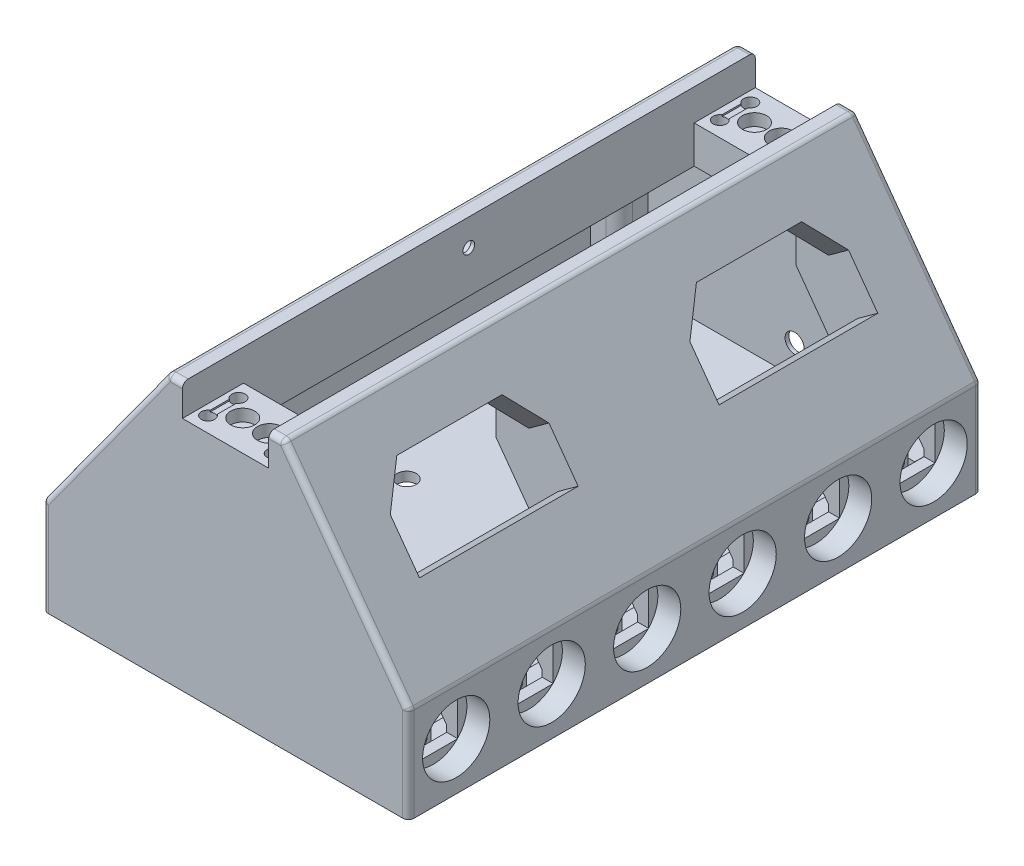
SolidWorks part; units mm, degrees
ref_plane "Front Plane" through (0, 0, 0) normal (0, 0, 1) x (1, 0, 0)
ref_plane "Top Plane" through (0, 0, 0) normal (0, 1, 0) x (1, 0, 0)
ref_plane "Right Plane" through (0, 0, 0) normal (1, 0, 0) x (0, 0, -1)
sketch "Sketch1" plane through (0, 0, 0) normal (0, 0, 1) x (1, 0, 0)
  line L0 (0, 0) -> (0, 70) construction
  line L1 (47.8944, 0) -> (-47.8944, 0)
  line L2 (-47.8944, 0) -> (-47.8944, 25)
  line L3 (-47.8944, 25) -> (-15.2, 70)
  line L4 (15.2, 70) -> (-15.2, 70) construction
  line L5 (45.8944, 2) -> (-45.8944, 2)
  line L6 (-45.8944, 2) -> (-45.8944, 23.4995)
  line L7 (-45.8944, 23.4995) -> (-25.1833, 52.0059)
  line L8 (11.3, 70) -> (11.3, 61.8)
  line L11 (-15.2, 70) -> (-11.3, 70)
  line L12 (-11.3, 70) -> (-11.3, 61.8)
  line L13 (-11.3, 61.8) -> (11.3, 61.8)
  line L14 (15.2, 70) -> (11.3, 70)
  line L16 (45.8944, 23.4995) -> (25.1833, 52.0059)
  line L17 (45.8944, 2) -> (45.8944, 23.4995)
  line L18 (47.8944, 25) -> (15.2, 70)
  line L19 (47.8944, 0) -> (47.8944, 25)
  line L20 (-25.1833, 52.0059) -> (25.1833, 52.0059)
  point P19 (0, 61.8)
  point P21 (0, 50.577)
  point P24 (0, 2)
  dimension "D1" = 15.2
  dimension "D2" = 54
  dimension "D3" = 8.2
  dimension "D4" = 2.5
  dimension "D5" = 2
  dimension "D6" = 25
  dimension "D7" = 70
  dimension "D8" = 47.8944
  dimension "D9" = 2
  dimension "D12" = 11.3
extrude "Boss-Extrude2" add sketch "Sketch1" along normal blind 150
sketch "Sketch3" plane through (0, 61.8, 0) normal (0, 1, 0) x (1, 0, 0)
  line L0 (11.3, -150) -> (11.3, 0) construction
  line L1 (11.3, -16) -> (-11.3, -16)
  line L2 (11.3, -16) -> (11.3, -134)
  line L3 (11.3, -134) -> (-11.3, -134)
  line L4 (-11.3, -16) -> (-11.3, -134)
  line L5 (-11.3, -150) -> (-11.3, 0) construction
  line L7 (-11.3, 0) -> (11.3, 0) construction
  line L8 (-8.6, -4) -> (-8.6, -12) construction
  line L9 (-11.3, -8) -> (0, -8) construction
  line L10 (0, -8) -> (0, 0) construction
  line L11 (-11.3, -75) -> (11.3, -75) construction
  circle A0 centre (-8.6, -12) radius 1.75
  circle A2 centre (-8.6, -4) radius 1.75
  circle A3 centre (8.6, -12) radius 1.75
  circle A4 centre (8.6, -4) radius 1.75
  circle A5 centre (8.6, -138) radius 1.75
  circle A6 centre (8.6, -146) radius 1.75
  circle A7 centre (-8.6, -146) radius 1.75
  circle A8 centre (-8.6, -138) radius 1.75
  circle A9 centre (-3.5, -8) radius 3 construction
  point P9 (11.3, -75)
  point P17 (-8.6, -8)
  dimension "D2" = 3.5
  dimension "D6" = 6
  dimension "D1" = 16
  dimension "D3" = 8
  dimension "D4" = 8
  dimension "D5" = 8.6
  dimension "D7" = 3.5
extrude "Cut-Extrude1" cut sketch "Sketch3" against normal up to next
ref_plane "Plane1" through (-12.3, 0, 0) normal (1, 0, 0) x (0, 0, -1)
ref_plane "Plane2" through (0, 0, 75) normal (0, 0, 1) x (1, 0, 0)
sketch "Sketch12" plane through (0, 0, 0) normal (0, 0, -1) x (-1, 0, 0)
  line L0 (-38.9919, 8) -> (-14.3, 41.9855)
  line L1 (-38.9919, 8) -> (-38.9919, 2)
  line L3 (-45.8944, 2) -> (45.8944, 2) construction
  line L4 (-47.8944, 25) -> (-15.2, 70) construction
  line L6 (-45.8944, 23.4995) -> (-25.1833, 52.0059) construction
  line L7 (-45.8944, 23.4995) -> (-25.1833, 52.0059)
  line L8 (-45.8944, 2) -> (-45.8944, 23.4995) construction
  line L9 (-45.8944, 2) -> (-45.8944, 23.4995)
  line L10 (-38.9919, 2) -> (-45.8944, 2)
  line L11 (-14.3, 41.9855) -> (-14.3, 52.0059)
  line L12 (25.1833, 52.0059) -> (-25.1833, 52.0059) construction
  line L13 (-11.3, 70) -> (-11.3, 61.8) construction
  line L14 (-25.1833, 52.0059) -> (-14.3, 52.0059)
  dimension "D1" = 17.1946
  dimension "D2" = 6
  dimension "D3" = 3
extrude "Boss-Extrude4" add sketch "Sketch12" against normal up to surface (150 mm away) up to face at (0, 25.8351, 150)
sketch "Sketch5" plane through (-11.3, 0, 0) normal (1, 0, 0) x (0, 0, -1)
  line L0 (-150, 70) -> (0, 70) construction
  line L1 (-75, 63) -> (-75, 70) construction
  circle A0 centre (-75, 63) radius 1.52
  dimension "D2" = 3.04
  dimension "D1" = 7
extrude "Cut-Extrude2" cut sketch "Sketch5" against normal through all
sketch "Sketch6" plane through (-11.3, 0, 0) normal (1, 0, 0) x (0, 0, -1)
  circle A0 centre (-75, 63) radius 1.52 construction
  circle A1 centre (-75, 63) radius 1.52
extrude "Cut-Extrude3" cut sketch "Sketch6" along normal offset from surface (26.6 mm away) 4 up to face at (11.3, 61.4015, 75) offset beyond the face yes
sketch "Sketch7" plane through (-12.3, 0, 0) normal (1, 0, 0) x (0, 0, -1)
  circle A0 centre (-75, 63) radius 1.52 construction
  circle A1 centre (-75, 63) radius 1.52 construction
  circle A2 centre (-75, 63) radius 2.8
  dimension "D1" = 5.6
extrude "Cut-Extrude4" cut sketch "Sketch7" against normal through all
sketch "Sketch10" plane through (-43.2355, 31.4124, 0) normal (-0.809, 0.5878, 0) x (0, 0, 1)
  line L0 (75, -7.9262) -> (75, 47.6969) construction
  line L1 (67.15, 32.6969) -> (82.85, 32.6969)
  line L2 (67.15, 32.6969) -> (67.15, 3.1969)
  line L3 (67.15, 3.1969) -> (82.85, 3.1969)
  line L4 (82.85, 32.6969) -> (82.85, 3.1969)
  line L5 (150, -7.9262) -> (0, -7.9262) construction
  line L6 (150, 47.6969) -> (0, 47.6969) construction
  point P10 (75, 32.6969)
  dimension "D1" = 29.5
  dimension "D2" = 15.7
  dimension "D3" = 15
extrude "Cut-Extrude5" cut sketch "Sketch10" against normal up to next
sketch "Sketch11" plane through (43.2355, 31.4124, 0) normal (0.809, 0.5878, 0) x (0, 0, -1)
  line L0 (-150, -7.9262) -> (-150, 47.6969) construction
  line L1 (-135, 34.6969) -> (-93.45, 34.6969)
  line L2 (-135, 34.6969) -> (-135, 12.6969)
  line L3 (-135, 12.6969) -> (-93.45, 12.6969)
  line L4 (-93.45, 34.6969) -> (-93.45, 12.6969)
  line L5 (-150, 47.6969) -> (0, 47.6969) construction
  dimension "D1" = 41.55
  dimension "D2" = 22
  dimension "D3" = 15
  dimension "D4" = 13
extrude "Cut-Extrude6" cut sketch "Sketch11" against normal up to next
sketch "Sketch13" plane through (-7.463, 10.272, 0) normal (-0.5878, 0.809, 0) x (0.809, 0.5878, 0)
  line L0 (36.2474, -135) -> (53.442, -135) construction
  line L1 (36.2474, -93.45) -> (46.942, -93.45)
  line L2 (36.2474, -93.45) -> (36.2474, -135)
  line L3 (36.2474, -135) -> (46.942, -135)
  line L4 (46.942, -93.45) -> (46.942, -135)
  line L5 (53.442, -135) -> (53.442, -93.45) construction
  dimension "D1" = 6.5
extrude "Cut-Extrude7" cut sketch "Sketch13" against normal blind 12
sketch "Sketch14" plane through (-20.3943, 28.0703, 0) normal (0.5878, -0.809, 0) x (0.809, 0.5878, 0)
  line L0 (46.942, 93.45) -> (53.442, 93.45) construction
  line L1 (53.442, 93.45) -> (46.942, 93.45)
  line L2 (53.442, 93.45) -> (53.442, 100.45)
  line L3 (53.442, 100.45) -> (46.942, 100.45)
  line L4 (46.942, 93.45) -> (46.942, 100.45)
  line L5 (53.442, 114.225) -> (36.2474, 114.225) construction
  line L6 (53.442, 93.45) -> (53.442, 135) construction
  line L7 (36.2474, 93.45) -> (36.2474, 135) construction
  line L8 (46.942, 135) -> (46.942, 128)
  line L9 (53.442, 128) -> (46.942, 128)
  line L10 (53.442, 135) -> (53.442, 128)
  line L11 (53.442, 135) -> (46.942, 135)
  dimension "D1" = 7
extrude "Boss-Extrude5" add sketch "Sketch14" along normal blind 9
sketch "Sketch18" plane through (47.8944, 0, 0) normal (1, 0, 0) x (0, 0, -1)
  line L0 (-150, 0) -> (-150, 25) construction
  line L1 (-137.5, 12.5) -> (-150, 12.5) construction
  line L2 (-150, 25) -> (0, 25) construction
  line L3 (-150, 25) -> (0, 25) construction
  circle A0 centre (-137.5, 12.5) radius 8.8
  dimension "D1" = 17.6
  dimension "D2" = 150
  dimension "D3" = 12.5
extrude "Cut-Extrude8" cut sketch "Sketch18" against normal blind 6
sketch "Sketch19" plane through (43.2355, 31.4124, 0) normal (0.809, 0.5878, 0) x (0, 0, -1)
  line L0 (-135, 25.6969) -> (-128, 34.6969)
  line L1 (-128, 34.6969) -> (-128, 25.6969)
  line L2 (-128, 25.6969) -> (-135, 25.6969)
  line L3 (-114.225, 34.6969) -> (-114.225, 12.6969) construction
  line L4 (-100.45, 34.6969) -> (-128, 34.6969) construction
  line L5 (-135, 12.6969) -> (-93.45, 12.6969) construction
  line L6 (-100.45, 34.6969) -> (-100.45, 25.6969)
  line L7 (-93.45, 25.6969) -> (-100.45, 34.6969)
  line L8 (-100.45, 25.6969) -> (-93.45, 25.6969)
extrude "Cut-Extrude9" cut sketch "Sketch19" against normal up to next
mirror "Mirror1" about plane through (0, 0, 75) normal (0, 0, 1) of "Boss-Extrude5", "Cut-Extrude9", "Cut-Extrude7", "Cut-Extrude6"
sketch "Sketch21" plane through (0, 61.8, 0) normal (0, 1, 0) x (1, 0, 0)
  line L0 (-6.85, -12) -> (-6.85, -4)
  line L1 (-10.35, -4) -> (-10.35, -12)
  line L2 (0, 0) -> (0, -16) construction
  line L3 (-11.3, 0) -> (11.3, 0) construction
  line L4 (11.3, -16) -> (-11.3, -16) construction
  line L5 (10.35, -4) -> (10.35, -12)
  line L6 (6.85, -12) -> (6.85, -4)
  circle A0 centre (-8.6, -4) radius 1.75 construction
  arc A1 (-10.35, -4) -> (-6.85, -4) centre (-8.6, -4) ccw
  circle A2 centre (-8.6, -12) radius 1.75 construction
  arc A3 (-6.85, -12) -> (-10.35, -12) centre (-8.6, -12) ccw
  arc A4 (6.85, -12) -> (10.35, -12) centre (8.6, -12) cw
  arc A5 (10.35, -4) -> (6.85, -4) centre (8.6, -4) cw
extrude "Cut-Extrude10" [suppressed] cut sketch "Sketch21" against normal blind 0.4
sketch "Sketch25" plane through (0, 0, 150) normal (0, 0, 1) x (1, 0, 0)
  line L10 (-11.3, 61.8) -> (-11.3, 70)
  line L11 (-11.3, 70) -> (-15.2, 70)
  line L12 (-15.2, 70) -> (-47.8944, 25)
  line L13 (-47.8944, 25) -> (-47.8944, 0)
  line L14 (-47.8944, 0) -> (47.8944, 0)
  line L15 (47.8944, 0) -> (47.8944, 25)
  line L16 (47.8944, 25) -> (15.2, 70)
  line L17 (15.2, 70) -> (11.3, 70)
  line L18 (11.3, 70) -> (11.3, 61.8)
  line L19 (11.3, 61.8) -> (-11.3, 61.8)
  line L20 (-11.3, 61.8) -> (-11.3, 70)
  line L21 (-11.3, 70) -> (-15.2, 70)
  line L22 (-15.2, 70) -> (-47.8944, 25)
  line L23 (-47.8944, 25) -> (-47.8944, 0)
  line L24 (-47.8944, 0) -> (47.8944, 0)
  line L25 (47.8944, 0) -> (47.8944, 25)
  line L26 (47.8944, 25) -> (15.2, 70)
  line L27 (15.2, 70) -> (11.3, 70)
  line L28 (11.3, 70) -> (11.3, 61.8)
  line L29 (11.3, 61.8) -> (-11.3, 61.8)
  dimension "D1" = 0
extrude "Boss-Extrude6" add sketch "Sketch25" against normal blind 1
mirror "Mirror3" about plane through (0, 0, 75) normal (0, 0, 1) of "Boss-Extrude6"
sketch "Sketch27" plane through (0, 2, 0) normal (0, 1, 0) x (1, 0, 0)
  line L0 (-41.8944, -145) -> (-41.8944, -149) construction
  line L1 (-45.8944, -149) -> (38.9919, -149) construction
  line L2 (-41.8944, -145) -> (-45.8944, -145) construction
  line L3 (-45.8944, -149) -> (-45.8944, -1) construction
  line L4 (-45.8944, -75) -> (34.8364, -75) construction
  line L5 (-15.8944, -1) -> (-15.8944, -149) construction
  line L8 (-41.8944, -5) -> (-45.8944, -5) construction
  line L9 (-41.8944, -141.5) -> (-45.8944, -141.5)
  line L10 (-38.3944, -145) -> (-38.3944, -149)
  line L11 (-45.8944, -141.5) -> (-45.8944, -149)
  line L12 (-45.8944, -149) -> (-38.3944, -149)
  line L13 (-41.8944, -5) -> (-41.8944, -1) construction
  line L14 (-45.8944, -1) -> (-38.3944, -1)
  line L15 (-45.8944, -8.5) -> (-45.8944, -1)
  line L16 (-38.3944, -5) -> (-38.3944, -1)
  line L17 (-41.8944, -8.5) -> (-45.8944, -8.5)
  line L18 (38.9919, -1) -> (-45.8944, -1) construction
  circle A0 centre (-41.8944, -145) radius 2
  arc A1 (-38.3944, -145) -> (-41.8944, -141.5) centre (-41.8944, -145) ccw
  arc A2 (-38.3944, -5) -> (-41.8944, -8.5) centre (-41.8944, -5) cw
  circle A3 centre (-41.8944, -5) radius 2
  dimension "D1" = 4
  dimension "D2" = 7
  dimension "D3" = 4
  dimension "D4" = 4
  dimension "D5" = 30
extrude "Boss-Extrude7" add sketch "Sketch27" along normal up to surface (27.005 mm away)
sketch "Sketch28" plane through (0, 2, 0) normal (0, 1, 0) x (1, 0, 0)
  line L4 (38.9919, -149) -> (38.9919, -1)
  line L5 (38.9919, -1) -> (-38.3944, -1)
  line L6 (-45.8944, -8.5) -> (-45.8944, -141.5)
  line L7 (-38.3944, -149) -> (38.9919, -149)
  line L8 (38.9919, -149) -> (38.9919, -1)
  line L9 (38.9919, -1) -> (-38.3944, -1)
  line L10 (-45.8944, -8.5) -> (-45.8944, -141.5)
  line L11 (-38.3944, -149) -> (38.9919, -149)
  line L16 (-45.8944, -141.5) -> (-41.8944, -141.5)
  line L18 (-45.8944, -141.5) -> (-41.8944, -141.5)
  line L20 (-38.3944, -145) -> (-38.3944, -149)
  line L22 (-38.3944, -145) -> (-38.3944, -149)
  line L24 (-38.3944, -1) -> (-38.3944, -5)
  line L25 (-38.3944, -1) -> (-38.3944, -5)
  line L26 (-41.8944, -8.5) -> (-45.8944, -8.5)
  line L27 (-41.8944, -8.5) -> (-45.8944, -8.5)
  arc A2 (-38.3944, -145) -> (-41.8944, -141.5) centre (-41.8944, -145) ccw
  arc A4 (-38.3944, -145) -> (-41.8944, -141.5) centre (-41.8944, -145) ccw
  arc A6 (-41.8944, -8.5) -> (-38.3944, -5) centre (-41.8944, -5) ccw
  arc A7 (-41.8944, -8.5) -> (-38.3944, -5) centre (-41.8944, -5) ccw
  dimension "D1" = 0
extrude "Cut-Extrude13" cut sketch "Sketch28" against normal through all
sketch "Sketch29" plane through (0, 2, 0) normal (0, 1, 0) x (1, 0, 0)
  circle A1 centre (-41.8944, -5) radius 2
  circle A2 centre (-41.8944, -5) radius 2
  circle A3 centre (-41.8944, -145) radius 2
  circle A4 centre (-41.8944, -145) radius 2
  dimension "D1" = 0
  dimension "D2" = 0
extrude "Cut-Extrude14" cut sketch "Sketch29" against normal through all
sketch "Sketch30" plane through (0, 0, 0) normal (0, -1, 0) x (1, 0, 0)
  line L0 (-38.3944, 149) -> (-45.8944, 149)
  line L1 (-45.8944, 149) -> (-45.8944, 141.5)
  line L3 (-45.8944, 8.5) -> (-45.8944, 141.5) construction
  line L4 (-38.3944, 145) -> (-38.3944, 149) construction
  line L5 (-38.3944, 145) -> (-38.3944, 149)
  line L6 (-45.8944, 141.5) -> (-41.8944, 141.5) construction
  line L7 (-45.8944, 141.5) -> (-41.8944, 141.5)
  line L8 (38.5, 75) -> (-38.5, 75) construction
  line L9 (-45.8944, 8.5) -> (-41.8944, 8.5)
  line L10 (-38.3944, 5) -> (-38.3944, 1)
  line L11 (-45.8944, 1) -> (-45.8944, 8.5)
  line L12 (-38.3944, 1) -> (-45.8944, 1)
  arc A0 (-41.8944, 141.5) -> (-38.3944, 145) centre (-41.8944, 145) ccw construction
  arc A1 (-41.8944, 141.5) -> (-38.3944, 145) centre (-41.8944, 145) ccw
  arc A2 (-41.8944, 8.5) -> (-38.3944, 5) centre (-41.8944, 5) cw
extrude "D" cut sketch "Sketch30" against normal blind 2.5
sketch "Sketch31" plane through (0, 0, 149) normal (0, 0, -1) x (-1, 0, 0)
  line L6 (45.8944, 0) -> (-38.9919, 0) construction
  line L7 (-38.9919, 0) -> (-37.1919, 0)
  line L8 (-38.9919, 0) -> (-38.9919, 3)
  line L9 (-38.9919, 3) -> (-37.5919, 3)
  line L10 (-37.1919, 0) -> (-37.1919, 2.6)
  arc A1 (-37.5919, 3) -> (-37.1919, 2.6) centre (-37.5919, 2.6) cw
  point P13 (-37.1919, 4.5)
  point P16 (-37.1919, 3)
  dimension "D1" = 3
  dimension "D3" = 1.8
extrude "Boss-Extrude8" add sketch "Sketch31" along normal blind 1.4
mirror "Mirror4" about plane through (0, 0, 75) normal (0, 0, 1) of "Boss-Extrude8"
sketch "Sketch33" plane through (0, 0, 1) normal (0, 0, 1) x (1, 0, 0)
  line L0 (0, 0) -> (0, 10) construction
  circle A0 centre (0, 10) radius 2.5
  dimension "D1" = 5
  dimension "D2" = 10
extrude "Cut-Extrude16" cut sketch "Sketch33" against normal through all
fillet "Fillet1" radius 1.5 16 edges at (-13.25, 70, 0) (-13.25, 70, 150) (13.25, 70, 0) (13.25, 70, 150) (47.8944, 12.5, 0) (47.8944, 12.5, 150) (-47.8944, 12.5, 0) (-47.8944, 12.5, 150) (-31.5472, 47.5, 0) (-31.5472, 47.5, 150) (31.5472, 47.5, 0) (31.5472, 47.5, 150) (47.8944, 25, 75) (-47.8944, 25, 75) (-15.2, 70, 75) (15.2, 70, 75)
sketch "Sketch34" plane through (0, 61.8, 0) normal (0, 1, 0) x (1, 0, 0)
  line L0 (-3.5, 0) -> (-3.5, -16) construction
  line L1 (-11.3, 0) -> (11.3, 0) construction
  line L2 (11.3, -16) -> (-11.3, -16) construction
  line L3 (3.5, -8) -> (-3.5, -8) construction
  line L4 (0, 0) -> (0, -8) construction
  circle A0 centre (-3.5, -8) radius 3.15
  circle A1 centre (3.5, -8) radius 3.15
  point P11 (0, -8)
  dimension "D1" = 6.3
  dimension "D2" = 7
  dimension "D3" = 8
extrude "Cut-Extrude17" cut sketch "Sketch34" against normal blind 3.15
mirror "Mirror6" about plane through (0, 0, 75) normal (0, 0, 1) of "Cut-Extrude17"
sketch "Sketch35" plane through (41.8944, 0, 0) normal (1, 0, 0) x (0, 0, -1)
  line L1 (-143.9, 18.675) -> (-131.1, 18.675)
  line L2 (-143.9, 18.675) -> (-143.9, 6.325)
  line L3 (-143.9, 6.325) -> (-131.1, 6.325)
  line L4 (-131.1, 18.675) -> (-131.1, 6.325)
  line L5 (-143.9, 18.675) -> (-131.1, 6.325) construction
  line L6 (-143.9, 6.325) -> (-131.1, 18.675) construction
  circle A0 centre (-137.5, 12.5) radius 8.8 construction
  point P0 (-137.5, 12.5)
  dimension "D1" = 12.35
  dimension "D2" = 12.8
extrude "Cut-Extrude18" cut sketch "Sketch35" against normal up to next
sketch "Sketch38" plane through (38.9919, 0, 0) normal (-1, 0, 0) x (0, 0, 1)
  line L1 (139.75, 4.63) -> (135.25, 4.63)
  line L2 (139.75, 4.63) -> (139.75, 18.675)
  line L3 (139.75, 18.675) -> (135.25, 18.675)
  line L4 (135.25, 4.63) -> (135.25, 18.675)
  line L5 (143.9, 6.325) -> (131.1, 6.325) construction
  line L6 (131.1, 18.675) -> (143.9, 18.675) construction
  line L7 (147.6, 0) -> (2.4, 0) construction
  point P8 (137.5, 6.325)
  point P9 (137.5, 4.63)
  dimension "D1" = 4.5
  dimension "D2" = 4.63
extrude "Boss-Extrude10" add sketch "Sketch38" along normal blind 5
sketch "Sketch39" plane through (38.9919, 0, 0) normal (1, 0, 0) x (0, 0, -1)
  line L0 (-137.5, 18.675) -> (-137.5, 6.325) construction
  line L1 (-139.75, 18.675) -> (-135.25, 18.675) construction
  line L2 (-139.75, 6.325) -> (-135.25, 6.325) construction
  line L3 (-135.25, 12.5) -> (-139.75, 12.5) construction
  line L4 (-135.25, 18.675) -> (-135.25, 6.325) construction
  line L5 (-139.75, 6.325) -> (-139.75, 18.675) construction
  circle A0 centre (-137.5, 17.425) radius 1.25
  circle A1 centre (-137.5, 7.575) radius 1.25
  dimension "D1" = 2.5
extrude "Cut-Extrude19" cut sketch "Sketch39" against normal blind 1.5
pattern_linear "LPattern1" count 6 spacing 25 along (0, 0, -1) of "Cut-Extrude8", "Cut-Extrude18", "Cut-Extrude19", "Boss-Extrude10"
sketch "Sketch40" plane through (0, 61.8, 0) normal (0, 1, 0) x (1, 0, 0)
  line L0 (7.6762, -5.4863) -> (7.6762, -10.5137)
  line L1 (8.6, -10.25) -> (8.6, -5.75) construction
  line L2 (9.5238, -5.4863) -> (9.5238, -10.5137)
  line L3 (0, -16) -> (0, 0) construction
  line L4 (11.3, -16) -> (-11.3, -16) construction
  line L5 (-11.3, 0) -> (11.3, 0) construction
  line L6 (-8.6, -10.25) -> (-8.6, -5.75) construction
  line L7 (-9.5238, -5.4863) -> (-9.5238, -10.5137)
  line L8 (-7.6762, -5.4863) -> (-7.6762, -10.5137)
  line L9 (-37.675, -75) -> (37.675, -75) construction
  line L10 (-8.6, -139.75) -> (-8.6, -144.25) construction
  line L11 (0, -134) -> (0, -150) construction
  line L12 (8.6, -139.75) -> (8.6, -144.25) construction
  line L13 (-7.6762, -144.5137) -> (-7.6762, -139.4863)
  line L14 (-9.5238, -144.5137) -> (-9.5238, -139.4863)
  line L15 (9.5238, -144.5137) -> (9.5238, -139.4863)
  line L16 (7.6762, -144.5137) -> (7.6762, -139.4863)
  circle A0 centre (8.6, -4) radius 1.75 construction
  circle A1 centre (8.6, -12) radius 1.75 construction
  arc A2 (7.6762, -5.4863) -> (9.5238, -5.4863) centre (8.6, -4) ccw
  arc A3 (9.5238, -10.5137) -> (7.6762, -10.5137) centre (8.6, -12) ccw
  arc A4 (-9.5238, -10.5137) -> (-7.6762, -10.5137) centre (-8.6, -12) cw
  arc A5 (-7.6762, -5.4863) -> (-9.5238, -5.4863) centre (-8.6, -4) cw
  arc A6 (-7.6762, -144.5137) -> (-9.5238, -144.5137) centre (-8.6, -146) ccw
  arc A7 (-9.5238, -139.4863) -> (-7.6762, -139.4863) centre (-8.6, -138) ccw
  arc A8 (9.5238, -139.4863) -> (7.6762, -139.4863) centre (8.6, -138) cw
  arc A9 (7.6762, -144.5137) -> (9.5238, -144.5137) centre (8.6, -146) cw
extrude "Cut-Extrude20" cut sketch "Sketch40" against normal blind 0.4
sketch "Sketch42" plane through (38.9919, 0, 0) normal (-1, 0, 0) x (0, 0, 1)
  line L0 (149, 8) -> (149, 3) construction
  line L1 (148.85, 3.08) -> (147.45, 3.08)
  line L2 (148.85, 3.08) -> (148.85, 6.08)
  line L3 (148.85, 6.08) -> (141.75, 6.08)
  line L4 (141.75, 4.33) -> (141.75, 6.08)
  line L5 (135.25, 4.63) -> (139.75, 4.63) construction
  line L6 (139.75, 4.63) -> (139.75, 6.325) construction
  line L7 (147.45, 3.08) -> (147.45, 0)
  line L8 (147.6, 0) -> (2.4, 0) construction
  line L9 (147.45, 0) -> (2.55, 0)
  line L10 (75, -37.675) -> (75, 37.675) construction
  line L11 (75, 0) -> (75, 4.33) construction
  line L12 (147.6, 3) -> (147.6, 0) construction
  line L13 (147.6, 3) -> (149, 3) construction
  line L14 (8.25, 4.33) -> (141.75, 4.33)
  line L16 (2.55, 3.08) -> (2.55, 0)
  line L17 (8.25, 4.33) -> (8.25, 6.08)
  line L18 (1.15, 6.08) -> (8.25, 6.08)
  line L19 (1.15, 3.08) -> (1.15, 6.08)
  line L20 (1.15, 3.08) -> (2.55, 3.08)
  dimension "D1" = 0.15
  dimension "D2" = 3
  dimension "D3" = 2
  dimension "D4" = 0.15
  dimension "D5" = 0.08
  dimension "D6" = 0.3
extrude "Boss-Extrude12" add sketch "Sketch42" along normal offset from surface (5.5 mm away) 4 from offset 0.3 separate body up to face at (37.1919, 1.3, 148.3) offset beyond the face yes
sketch "Sketch41" plane through (0, 0, 0) normal (0, -1, 0) x (1, 0, 0)
  line L0 (-45.7944, 1.2) -> (36.9919, 1.2)
  line L6 (36.9919, 148.8) -> (-45.7944, 148.8)
  line L7 (-45.7944, 148.8) -> (-45.7944, 1.2)
  line L8 (33.1919, 147.45) -> (33.1919, 2.55)
  line L9 (33.1919, 147.45) -> (33.1919, 2.55) construction
  line L10 (36.9919, 2.55) -> (33.1919, 2.55)
  line L11 (-45.8944, 1) -> (-45.8944, 149) construction
  line L12 (37.1919, 1) -> (-45.8944, 1) construction
  line L13 (-45.8944, 149) -> (37.1919, 149) construction
  line L14 (36.9919, 2.55) -> (36.9919, 1.2)
  line L15 (33.1919, 2.55) -> (38.6919, 2.55) construction
  line L17 (37.1919, 2.4) -> (37.1919, 1) construction
  line L19 (36.9919, 147.45) -> (36.9919, 148.8)
  line L20 (33.1919, 147.45) -> (38.6919, 147.45) construction
  line L21 (36.9919, 147.45) -> (33.1919, 147.45)
  dimension "D1" = 0.2
  dimension "D2" = 0.1
  dimension "D3" = 0.2
  dimension "D4" = 0.2
extrude "Boss-Extrude13" add sketch "Sketch41" against normal offset from surface (2.45 mm away) 0.05 up to face at (-41.8944, 2.5, 7)
sketch "Sketch44" plane through (0, 2.5, 0) normal (0, -1, 0) x (-1, 0, 0)
  circle A0 centre (41.8944, -5) radius 1.58
  circle A1 centre (41.8944, -145) radius 1.58
  dimension "D1" = 3.16
  dimension "D2" = 3.16
extrude "Cut-Extrude22" cut sketch "Sketch44" along normal up to next
sketch "Sketch45" plane through (0, 0, 0) normal (0, -1, 0) x (1, 0, 0)
  line L1 (37.675, 75) -> (-37.675, 75) construction
  circle A0 centre (-27.5579, 75) radius 2.5
  dimension "D1" = 5
extrude "Cut-Extrude23" cut sketch "Sketch45" against normal up to next (2.45 mm away)
ref_plane "Plane3" through (-45.7944, 0, 1.2) normal (1, 0, 0) x (0, 0, -1)
sketch "Sketch47" plane through (0, 0, 0) normal (0, -1, 0) x (1, 0, 0)
  line L0 (-37.7944, 9.8541) -> (-42.7944, 9.8541) construction
  line L1 (-37.7944, 7.8541) -> (-42.7944, 7.8541)
  line L2 (-37.7944, 11.8541) -> (-42.7944, 11.8541)
  line L3 (-45.7944, -21.5662) -> (-45.7944, 23.9662) construction
  arc A0 (-37.7944, 7.8541) -> (-37.7944, 11.8541) centre (-37.7944, 9.8541) ccw
  arc A1 (-42.7944, 11.8541) -> (-42.7944, 7.8541) centre (-42.7944, 9.8541) ccw
  point P2 (-40.2944, 9.8541)
  point P7 (-41.4876, 10.2145)
  dimension "D1" = 2
  dimension "D2" = 3
  dimension "D3" = 5
extrude "Boss-Extrude14" add sketch "Sketch47" along normal blind 3.5 separate body
equation "\"D3@Sketch18\"=\"D2@Sketch18\"/12"
equation "\"D3@LPattern1\"=150/6"
equation "\"D2@Sketch44\"=\"D1@Sketch44\""
